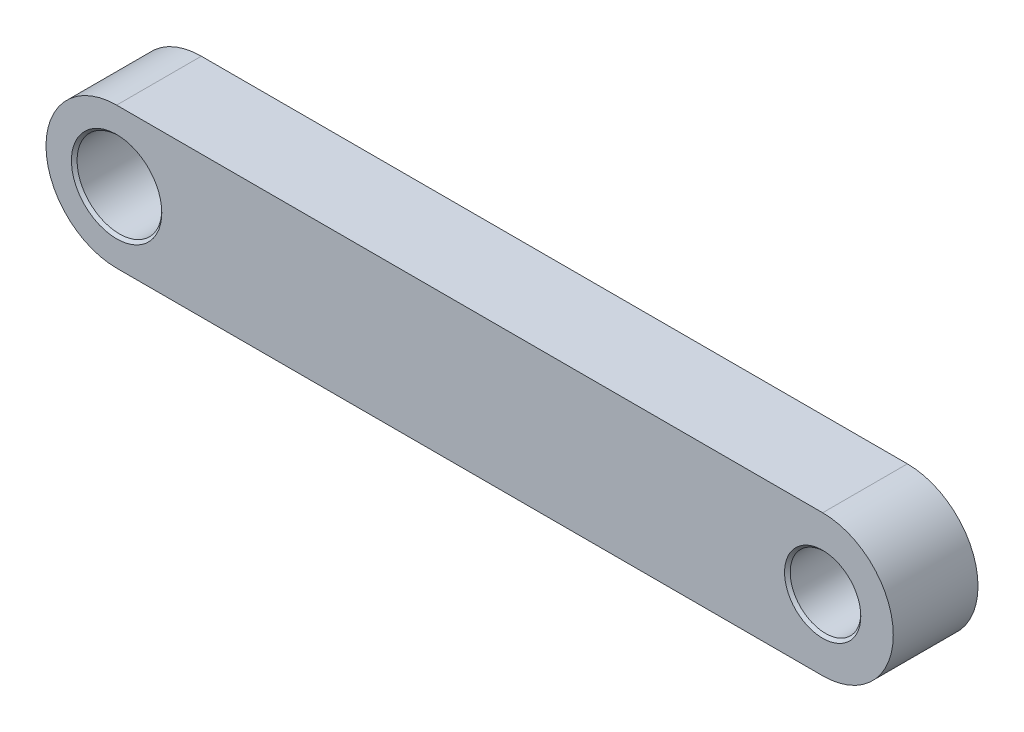
SolidWorks part; units mm, degrees
material "45"
ref_plane "Front Plane" through (0, 0, 0) normal (0, 0, 1) x (1, 0, 0)
ref_plane "Top Plane" through (0, 0, 0) normal (0, 1, 0) x (1, 0, 0)
ref_plane "Right Plane" through (0, 0, 0) normal (1, 0, 0) x (0, 0, -1)
sketch "Sketch1" plane through (0, 0, 0) normal (0, 0, 1) x (1, 0, 0)
  line L0 (0, 0) -> (50, 0) construction
  line L1 (0, 5) -> (50, 5)
  line L2 (0, -5) -> (50, -5)
  arc A0 (0, 5) -> (0, -5) centre (0, 0) ccw
  arc A1 (50, -5) -> (50, 5) centre (50, 0) ccw
  circle A2 centre (50, 0) radius 2.5
  circle A3 centre (0, 0) radius 3
  point P3 (25, 0)
  dimension "D1" = 5
  dimension "D3" = 6
  dimension "D4" = 5
  dimension "D2" = 50
extrude "Boss-Extrude1" add sketch "Sketch1" along normal mid plane 6
sketch "Sketch2" plane through (0, 0, 3) normal (0, 0, 1) x (1, 0, 0)
  line L0 (50, 5) -> (0, 5) construction
  line L1 (4.3818, 3) -> (45.6182, 3)
  line L3 (4.3818, -3) -> (45.6182, -3)
  line L5 (0, -5) -> (50, -5) construction
  arc A0 (4.2133, -2.6923) -> (4.2133, 2.6923) centre (0, 0) ccw
  arc A1 (45.7867, 2.6923) -> (45.7867, -2.6923) centre (50, 0) ccw
  arc A2 (0, 5) -> (0, -5) centre (0, 0) ccw construction
  arc A4 (50, -5) -> (50, 5) centre (50, 0) ccw construction
  arc A5 (45.7867, 2.6923) -> (45.6182, 3) centre (45.6182, 2.8) ccw
  arc A6 (45.7867, -2.6923) -> (45.6182, -3) centre (45.6182, -2.8) cw
  arc A7 (4.2133, -2.6923) -> (4.3818, -3) centre (4.3818, -2.8) ccw
  arc A8 (4.2133, 2.6923) -> (4.3818, 3) centre (4.3818, 2.8) cw
  dimension "D3" = 0.2
  dimension "D1" = 2
  dimension "D2" = 2
extrude "Cut-Extrude1" [suppressed] cut sketch "Sketch2" against normal blind 2
mirror "Mirror1" [suppressed] about plane through (0, 0, 0) normal (0, 0, 1)
chamfer "倒角1" distance 0.2 angle 45 4 edges at (3, 0, -3) (52.5, 0, -3) (52.5, 0, 3) (3, 0, 3)
